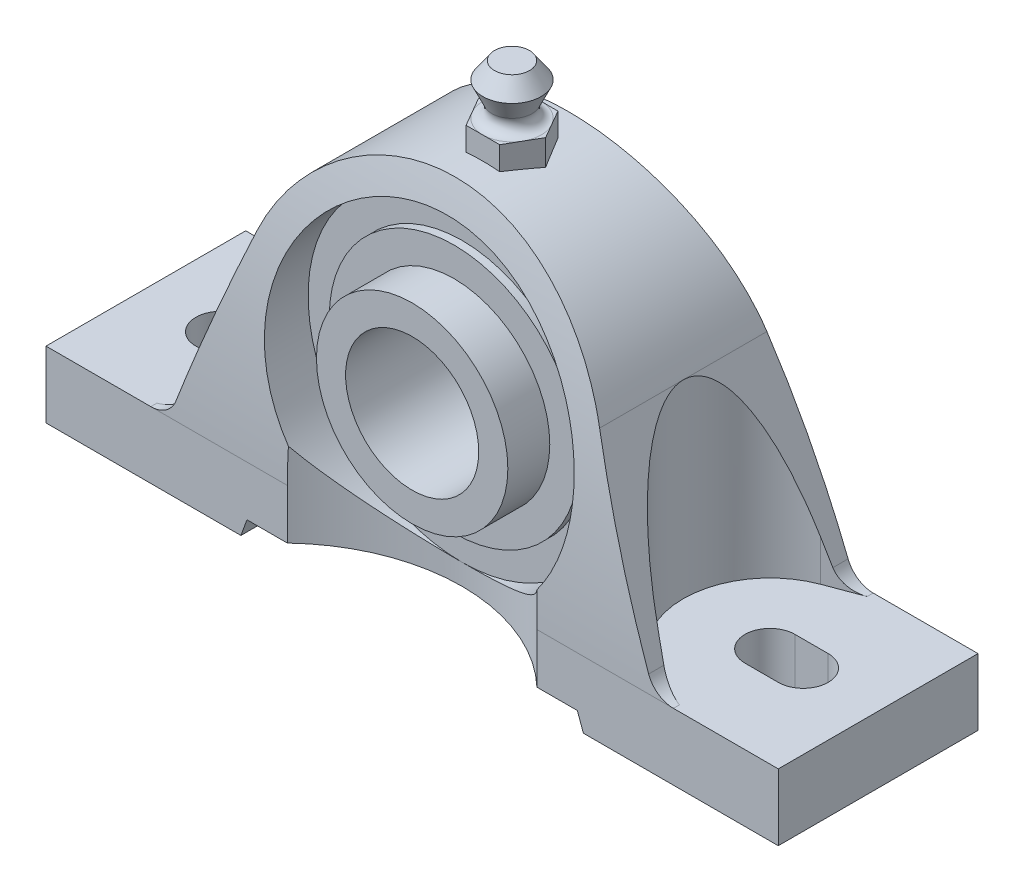
SolidWorks part; units mm, degrees
ref_plane "Front" through (0, 0, 0) normal (0, 0, 1) x (1, 0, 0)
ref_plane "Top" through (0, 0, 0) normal (0, 1, 0) x (1, 0, 0)
ref_plane "Right" through (0, 0, 0) normal (1, 0, 0) x (0, 0, -1)
sketch "Sketch1" plane through (0, 0, 0) normal (0, 0, 1) x (1, 0, 0)
  line L0 (-32.6693, 12.348) -> (-45.0956, -20.5286) construction
  line L1 (-49.8475, -23.8125) -> (-69.85, -23.8125) construction
  line L2 (-69.85, -23.8125) -> (-69.85, -36.5125) construction
  line L3 (-69.85, -36.5125) -> (-32.6693, -36.5125) construction
  line L4 (-32.6693, -36.5125) -> (-31.5137, -33.3375) construction
  line L5 (-31.5137, -33.3375) -> (31.5137, -33.3375) construction
  line L6 (0, 0) -> (0, -36.5125) construction
  line L7 (31.5137, -33.3375) -> (32.6693, -36.5125) construction
  line L8 (32.6693, -36.5125) -> (69.85, -36.5125) construction
  line L9 (69.85, -36.5125) -> (69.85, -23.8125) construction
  line L10 (69.85, -23.8125) -> (49.8475, -23.8125) construction
  line L11 (45.0956, -20.5286) -> (32.6693, 12.348) construction
  line L12 (-32.6693, 12.348) -> (-32.6693, -36.5125) construction
  line L13 (0, 12.7) -> (0, 18.2563) construction
  line L14 (-29.3688, 0) -> (-29.3687, -36.5125) construction
  line L15 (0, 18.2563) -> (0, 23.8125) construction
  line L16 (0, 23.8125) -> (0, 29.3688) construction
  line L17 (0, 29.3688) -> (0, 34.925) construction
  line L18 (-23.8125, 0) -> (-23.8125, -36.5125) construction
  circle A0 centre (0, 0) radius 12.7
  circle A1 centre (0, 0) radius 18.2563
  arc A2 (32.6693, 12.348) -> (-32.6693, 12.348) centre (0, 0) ccw construction
  arc A3 (-45.0956, -20.5286) -> (-49.8475, -23.8125) centre (-49.8475, -18.7325) cw construction
  arc A4 (49.8475, -23.8125) -> (45.0956, -20.5286) centre (49.8475, -18.7325) cw construction
  circle A5 centre (0, 0) radius 23.8125 construction
  circle A6 centre (0, 0) radius 29.3688 construction
  point P21 (0, -29.3688)
  dimension "Shaft Dia" = 25.4
  dimension "D10" = 5.08
  dimension "D Overall Height" = 71.4375
  dimension "A Center Height" = 36.5125
  dimension "Base Height" = 12.7
  dimension "B Overall Length" = 139.7
  dimension "D7" = 3.175
  dimension "D8" = 20
  dimension "D2" = 99.695
sketch "Sketch2" plane through (0, 0, 0) normal (0, 0, 1) x (1, 0, 0)
  line L0 (-32.6693, 12.348) -> (-45.0956, -20.5286) construction
  line L1 (-49.8475, -23.8125) -> (-69.85, -23.8125) construction
  line L2 (-69.85, -23.8125) -> (-69.85, -36.5125) construction
  line L3 (-69.85, -36.5125) -> (-32.6693, -36.5125) construction
  line L4 (-32.6693, -36.5125) -> (-31.5137, -33.3375) construction
  line L5 (-31.5137, -33.3375) -> (31.5137, -33.3375) construction
  line L6 (31.5137, -33.3375) -> (32.6693, -36.5125) construction
  line L7 (32.6693, -36.5125) -> (69.85, -36.5125) construction
  line L8 (69.85, -36.5125) -> (69.85, -23.8125) construction
  line L9 (69.85, -23.8125) -> (49.8475, -23.8125) construction
  line L10 (45.0956, -20.5286) -> (32.6693, 12.348) construction
  line L11 (-32.6693, 12.348) -> (-45.0956, -20.5286)
  line L12 (-49.8475, -23.8125) -> (-69.85, -23.8125)
  line L13 (-69.85, -23.8125) -> (-69.85, -36.5125)
  line L14 (-69.85, -36.5125) -> (-32.6693, -36.5125)
  line L15 (-32.6693, -36.5125) -> (-31.5137, -33.3375)
  line L16 (-31.5137, -33.3375) -> (31.5137, -33.3375)
  line L17 (31.5137, -33.3375) -> (32.6693, -36.5125)
  line L18 (32.6693, -36.5125) -> (69.85, -36.5125)
  line L19 (69.85, -36.5125) -> (69.85, -23.8125)
  line L20 (69.85, -23.8125) -> (49.8475, -23.8125)
  line L21 (45.0956, -20.5286) -> (32.6693, 12.348)
  arc A0 (-49.8475, -23.8125) -> (-45.0956, -20.5286) centre (-49.8475, -18.7325) ccw construction
  arc A1 (45.0956, -20.5286) -> (49.8475, -23.8125) centre (49.8475, -18.7325) ccw construction
  arc A2 (32.6693, 12.348) -> (-32.6693, 12.348) centre (0, 0) ccw construction
  arc A3 (-49.8475, -23.8125) -> (-45.0956, -20.5286) centre (-49.8475, -18.7325) ccw
  arc A4 (45.0956, -20.5286) -> (49.8475, -23.8125) centre (49.8475, -18.7325) ccw
  arc A5 (32.6693, 12.348) -> (-32.6693, 12.348) centre (0, 0) ccw
  circle A6 centre (0, 0) radius 18.2563 construction
  circle A7 centre (0, 0) radius 18.2563
extrude "Extrude2" add sketch "Sketch2" along normal mid plane 38.1 separate body
sketch "Sketch3" plane through (0, 0, 0) normal (0, 1, 0) x (1, 0, 0)
  line L0 (49.2125, 0) -> (55.5625, 0) construction
  line L1 (-49.2125, 0) -> (-55.5625, 0) construction
  line L2 (-55.5625, 4.7625) -> (-49.2125, 4.7625)
  line L3 (-55.5625, -4.7625) -> (-49.2125, -4.7625)
  line L4 (49.2125, -4.7625) -> (55.5625, -4.7625)
  line L5 (49.2125, 4.7625) -> (55.5625, 4.7625)
  line L6 (-49.2125, 0) -> (49.2125, 0) construction
  arc A0 (55.5625, 4.7625) -> (55.5625, -4.7625) centre (55.5625, 0) cw
  arc A1 (49.2125, 4.7625) -> (49.2125, -4.7625) centre (49.2125, 0) ccw
  arc A2 (-49.2125, -4.7625) -> (-49.2125, 4.7625) centre (-49.2125, 0) ccw
  arc A3 (-55.5625, 4.7625) -> (-55.5625, -4.7625) centre (-55.5625, 0) ccw
  point P15 (-52.3875, 0)
  point P16 (52.3875, 0)
  dimension "F Hole size" = 9.525
  dimension "Slot length" = 15.875
  dimension "Center to Center" = 104.775
extrude "Cut-Extrude1" cut sketch "Sketch3" against normal through all and the other way through all
sketch "Sketch4" plane through (0, 0, 0) normal (0, 1, 0) x (1, 0, 0)
  line L0 (-49.2125, 0) -> (-55.5625, 0) construction
  line L1 (49.2125, 0) -> (55.5625, 0) construction
  line L2 (-49.2125, 0) -> (-55.5625, 0) construction
  line L3 (49.2125, 0) -> (55.5625, 0) construction
  line L4 (43.4075, 15.4913) -> (69.85, 25.4)
  line L5 (69.85, 25.4) -> (69.85, -25.4)
  line L6 (69.85, -25.4) -> (43.4075, -15.4913)
  line L7 (-43.4075, -15.4913) -> (-69.85, -25.4)
  line L8 (-69.85, -25.4) -> (-69.85, 25.4)
  line L9 (-69.85, 25.4) -> (-43.4075, 15.4913)
  line L10 (69.85, -19.05) -> (69.85, 19.05) construction
  line L12 (-32.6693, -19.05) -> (-32.6693, 19.05) construction
  line L13 (0, 15.4913) -> (0, -15.4913) construction
  line L14 (0, -15.4913) -> (-43.4075, -15.4913) construction
  line L15 (-43.4075, 15.4913) -> (0, 15.4913) construction
  line L18 (-69.85, -19.05) -> (-69.85, 19.05) construction
  line L19 (-49.8475, 19.05) -> (-69.85, 19.05) construction
  arc A0 (43.4075, 15.4913) -> (43.4075, -15.4913) centre (49.2125, 0) ccw
  arc A1 (-43.4075, -15.4913) -> (-43.4075, 15.4913) centre (-49.2125, 0) ccw
  dimension "D1" = 6.35
extrude "Cut-Extrude2" cut sketch "Sketch4" against normal up to surface and the other way through all
sketch "Sketch5" plane through (0, 0, 0) normal (1, 0, 0) x (0, 0, -1)
  line L0 (-19.05, -23.8125) -> (-10.795, 34.925) construction
  line L1 (-10.795, 34.925) -> (-19.05, 34.925)
  line L2 (-19.05, 34.925) -> (-19.05, -23.8125)
  line L3 (-19.05, -23.8125) -> (19.05, -23.8125) construction
  line L4 (-19.05, -20.5286) -> (-19.05, 12.348) construction
  line L5 (19.05, 34.925) -> (-19.05, 34.925) construction
  line L6 (-10.795, 34.925) -> (-9.525, 34.925) construction
  line L7 (19.05, 34.925) -> (-19.05, 34.925) construction
  arc A0 (-10.795, 34.925) -> (-19.05, -23.8125) centre (194.047, -23.8125) ccw
  dimension "D1" = 8
  dimension "D2" = 1.27
extrude "Cut-Extrude3" cut sketch "Sketch5" against normal through all and the other way through all
sketch "Sketch10" plane through (0, 0, 19.05) normal (0, 0, 1) x (1, 0, 0)
  circle A0 centre (0, 0) radius 29.3688 construction
  circle A1 centre (0, 0) radius 29.3688
extrude "Cut-Extrude5" cut sketch "Sketch10" against normal up to vertex (9.525 mm away) up to point (0, 34.925, 9.525)
mirror "Mirror1" about plane through (0, 0, 0) normal (0, 0, 1) of "Cut-Extrude5", "Cut-Extrude3"
sketch "Sketch9" plane through (0, -36.5125, 0) normal (0, -1, 0) x (1, 0, 0)
  line L0 (23.8125, 19.05) -> (-23.8125, 19.05)
  line L1 (-49.8475, 19.05) -> (-69.85, 19.05) construction
  line L2 (0, 0) -> (48.5705, 0) construction
  line L3 (23.8125, -19.05) -> (-23.8125, -19.05)
  line L4 (-23.8125, 19.05) -> (-23.8125, 0) construction
  line L5 (29.3688, 9.525) -> (-29.3687, 9.525) construction
  arc A0 (23.8125, 19.05) -> (-23.8125, 19.05) centre (0, 44.0531) cw
  arc A1 (23.8125, -19.05) -> (-23.8125, -19.05) centre (0, -44.0531) ccw
extrude "Cut-Extrude4" cut sketch "Sketch9" against normal up to vertex (36.5125 mm away) up to point (0, 0, 0)
sketch "Sketch11" plane through (0, 0, 0) normal (0, 0, 1) x (1, 0, 0)
  circle A1 centre (0, 0) radius 23.8125 construction
  circle A2 centre (0, 0) radius 23.8125
  circle A3 centre (0, 0) radius 18.2563 construction
  circle A4 centre (0, 0) radius 18.2563
extrude "Boss-Extrude2" add sketch "Sketch11" along normal offset from surface 1.524 and the other way offset from surface (11.049 mm away) 1.524 up to face at (29.3688, 0, 9.525) offset beyond the face yes other way up to face at (29.3688, 0, -9.525)
sketch "Sketch8" plane through (0, 0, 19.05) normal (0, 0, 1) x (1, 0, 0)
  circle A0 centre (0, 0) radius 18.2563 construction
  circle A1 centre (0, 0) radius 12.7 construction
  circle A2 centre (0, 0) radius 18.2563
  circle A3 centre (0, 0) radius 12.7
extrude "Boss-Extrude1" add sketch "Sketch8" against normal blind 34.925 separate body
sketch "Sketch6" plane through (0, 0, 0) normal (0, 0, 1) x (1, 0, 0)
  line L0 (0, 0) -> (0, 34.925) construction
  line L1 (0, 0) -> (12.7, 0) construction
  line L2 (0, 0) -> (0, 34.925) construction
  line L4 (0, 34.925) -> (0, 44.9013) construction
  line L5 (0, 34.4802) -> (-5.5563, 34.4802)
  line L6 (-5.5563, 34.4802) -> (-5.5563, 39.2427)
  line L7 (-3.8466, 41.9263) -> (-5.5563, 45.5927)
  line L8 (-5.5563, 45.5927) -> (-3.3331, 48.7677)
  line L9 (-3.3331, 48.7677) -> (0, 48.7677)
  line L10 (0, 48.7677) -> (0, 34.4802)
  circle A0 centre (0, 0) radius 12.7 construction
  arc A1 (32.6693, 12.348) -> (-32.6693, 12.348) centre (0, 0) ccw construction
  arc A2 (-5.5563, 39.2427) -> (-3.8466, 41.9263) centre (-5.5563, 41.1291) ccw
  dimension "D1" = 90
  dimension "D2" = 14.2875
  dimension "D3" = 11.1125
  dimension "D4" = 4.7625
  dimension "D5" = 55
  dimension "D6" = 3.175
  dimension "D7" = 120
revolve "Revolve1" add sketch "Sketch6" angle 360 about L4
sketch "Sketch7" plane through (0, 34.4802, 0) normal (0, -1, 0) x (1, 0, 0)
  line L1 (-3.2079, 5.5562) -> (-6.4158, 0)
  line L2 (-6.4158, 0) -> (-3.2079, -5.5562)
  line L3 (-3.2079, -5.5562) -> (3.2079, -5.5562)
  line L4 (3.2079, -5.5562) -> (6.4158, 0)
  line L5 (6.4158, 0) -> (3.2079, 5.5562)
  line L6 (3.2079, 5.5562) -> (-3.2079, 5.5562)
  circle A0 centre (0, 0) radius 5.5562 construction
  circle A1 centre (0, 0) radius 5.5563 construction
extrude "Extrude3" add sketch "Sketch7" against normal up to vertex (4.7625 mm away) and the other way up to surface
equation "\"D7@Sketch1\" = \"Base Height@Sketch1\"/4"
equation "\"D10@Sketch1\"=\"Base Height@Sketch1\"/2.5"
equation "\"D2@Sketch1\" = \"Center to Center@Sketch3\"-\"D10@Sketch1\""
